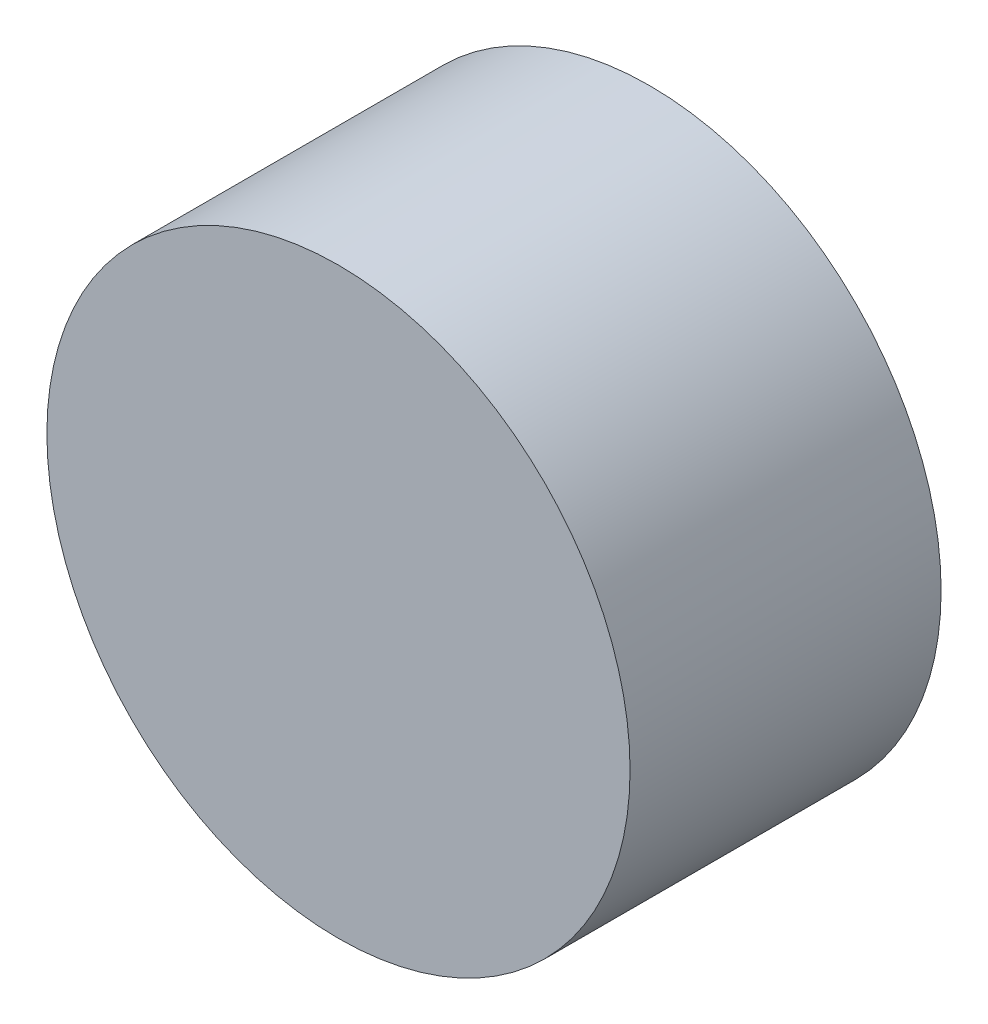
SolidWorks part; units mm, degrees
ref_plane "Ebene vorne" through (0, 0, 0) normal (0, 0, 1) x (1, 0, 0)
ref_plane "Ebene oben" through (0, 0, 0) normal (0, 1, 0) x (1, 0, 0)
ref_plane "Ebene rechts" through (0, 0, 0) normal (1, 0, 0) x (0, 0, -1)
sketch "Skizze1" plane through (0, 0, 0) normal (0, 0, 1) x (1, 0, 0)
  circle A0 centre (0, 0) radius 30
  dimension "D1" = 60
extrude "Aufsatz-Linear austragen1" add sketch "Skizze1" along normal blind 32
sketch "Skizze2" plane through (0, 0, 0) normal (0, 0, -1) x (-1, 0, 0)
  circle A0 centre (0, 0) radius 14.9966
extrude "Aufsatz-Linear austragen2" add sketch "Skizze2" along normal blind 2
sketch "Skizze3" plane through (0, 0, -2) normal (0, 0, -1) x (-1, 0, 0)
  circle A0 centre (0, 0) radius 4.75
  dimension "D1" = 9.5
extrude "Aufsatz-Linear austragen3" add sketch "Skizze3" along normal blind 10
sketch "Skizze4" plane through (0, 0, -12) normal (0, 0, -1) x (-1, 0, 0)
  circle A0 centre (0, 0) radius 4
  dimension "D1" = 8
extrude "Schnitt-Linear austragen1" cut sketch "Skizze4" against normal blind 10
